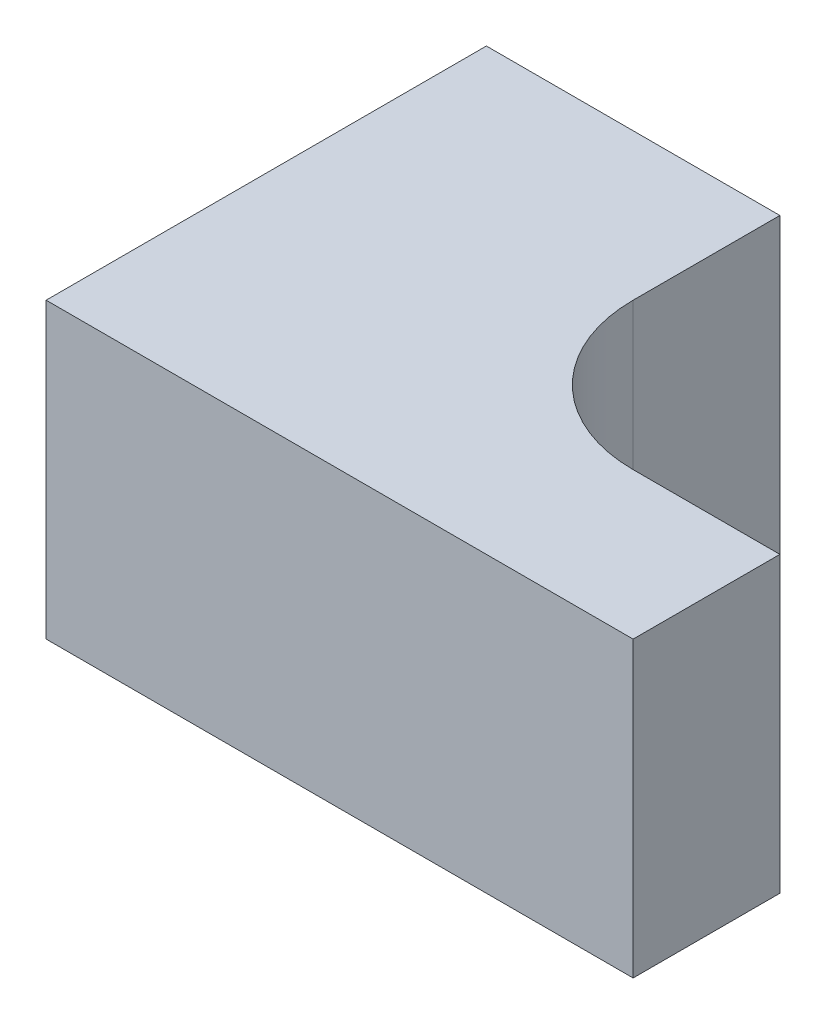
SolidWorks part; units mm, degrees
ref_plane "Přední rovina" through (0, 0, 0) normal (0, 0, 1) x (1, 0, 0)
ref_plane "Horní rovina" through (0, 0, 0) normal (0, 1, 0) x (1, 0, 0)
ref_plane "Pravá rovina" through (0, 0, 0) normal (1, 0, 0) x (0, 0, -1)
sketch "Sketch2" plane through (0, 0, 0) normal (0, 1, 0) x (1, 0, 0)
  line L0 (0, 0) -> (0, -10)
  line L1 (10, -20) -> (20, -20)
  line L2 (20, -20) -> (20, -30)
  line L3 (20, -30) -> (-20, -30)
  line L4 (-20, -30) -> (-20, 0)
  line L5 (-20, 0) -> (0, 0)
  arc A0 (0, -10) -> (10, -20) centre (10, -10) ccw
  dimension "D2" = 10
  dimension "D1" = 20
  dimension "D3" = 10
  dimension "D4" = 10
  dimension "D5" = 10
extrude "Boss-Extrude1" add sketch "Sketch2" along normal blind 20
equation "\"R\"= 10"
equation "\"D2@Sketch2\"=\"R\""
equation "\"D1@Sketch2\"=\"R\" *2"
equation "\"D3@Sketch2\"=\"R\" * 1"
equation "\"D5@Sketch2\"=\"R\""
equation "\"D4@Sketch2\"=\"R\""
